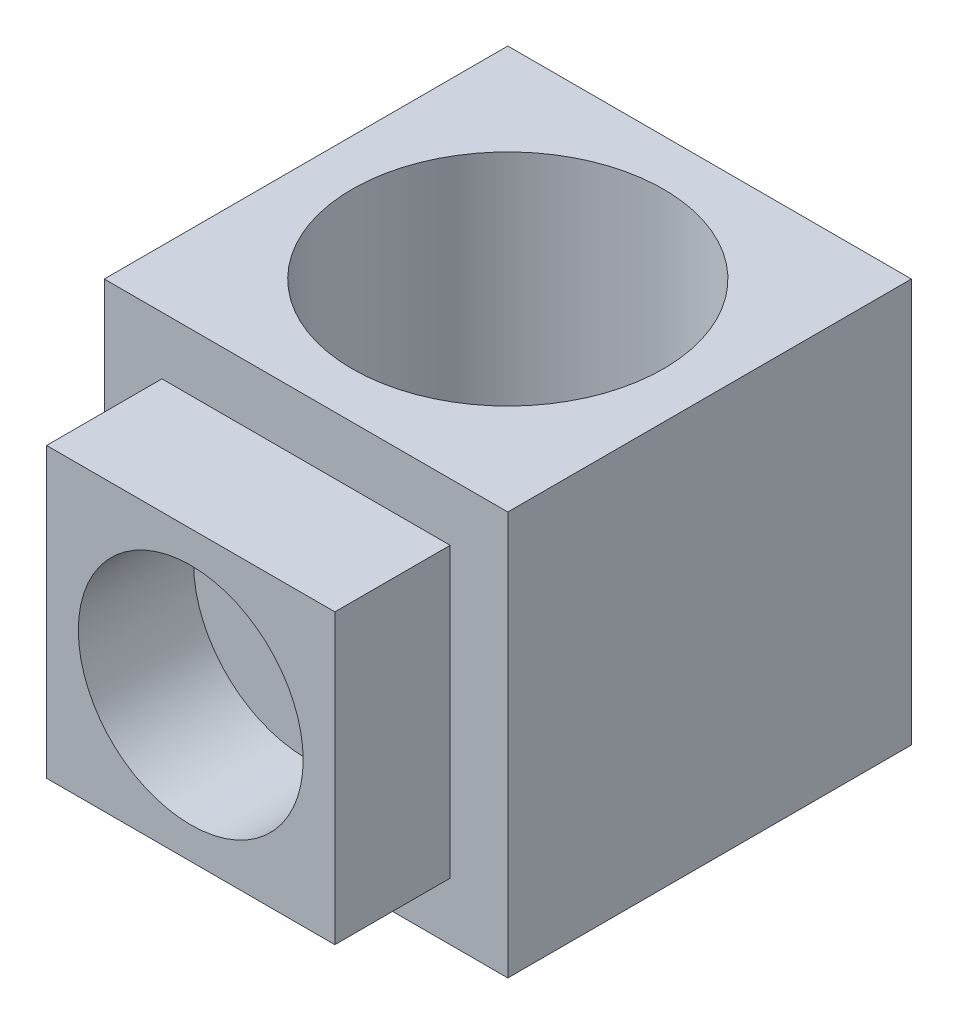
SolidWorks part; units mm, degrees
ref_plane "前视基准面" through (0, 0, 0) normal (0, 0, 1) x (1, 0, 0)
ref_plane "上视基准面" through (0, 0, 0) normal (0, 1, 0) x (1, 0, 0)
ref_plane "右视基准面" through (0, 0, 0) normal (1, 0, 0) x (0, 0, -1)
other "Configuration Table"
sketch "草图1" plane through (0, 0, 0) normal (0, 1, 0) x (1, 0, 0)
  line L1 (0, 0) -> (14, 0)
  line L2 (0, 0) -> (0, 14)
  line L3 (0, 14) -> (14, 14)
  line L4 (14, 0) -> (14, 14)
  dimension "D1" = 14
  dimension "D2" = 14
extrude "凸台-拉伸1" add sketch "草图1" along normal blind 14
sketch "草图2" plane through (0, 0, 0) normal (0, 0, 1) x (1, 0, 0)
  line L0 (0, 14) -> (0, 0) construction
  line L1 (2, 12) -> (12, 12)
  line L2 (2, 12) -> (2, 2)
  line L3 (2, 2) -> (12, 2)
  line L4 (12, 12) -> (12, 2)
  line L5 (0, 14) -> (14, 14) construction
  line L6 (2, 7) -> (12, 7) construction
  line L8 (7, 12) -> (7, 2) construction
  circle A0 centre (7, 7) radius 3.9
  dimension "D5" = 7.8
  dimension "D1" = 10
  dimension "D2" = 10
  dimension "D3" = 2
  dimension "D4" = 2
extrude "凸台-拉伸2" add sketch "草图2" along normal blind 4
sketch "草图3" plane through (0, 14, 0) normal (0, 1, 0) x (1, 0, 0)
  line L0 (7, 14) -> (7, 0) construction
  line L1 (14, 14) -> (0, 14) construction
  line L2 (12, 0) -> (2, 0) construction
  line L4 (0, 14) -> (0, 0) construction
  line L5 (0, 7) -> (14, 7) construction
  line L6 (14, 0) -> (14, 14) construction
  circle A0 centre (7, 7) radius 5.4
  dimension "D1" = 10.8
extrude "切除-拉伸1" cut sketch "草图3" against normal up to surface (14 mm away) up to face at (7, 0, -7)
